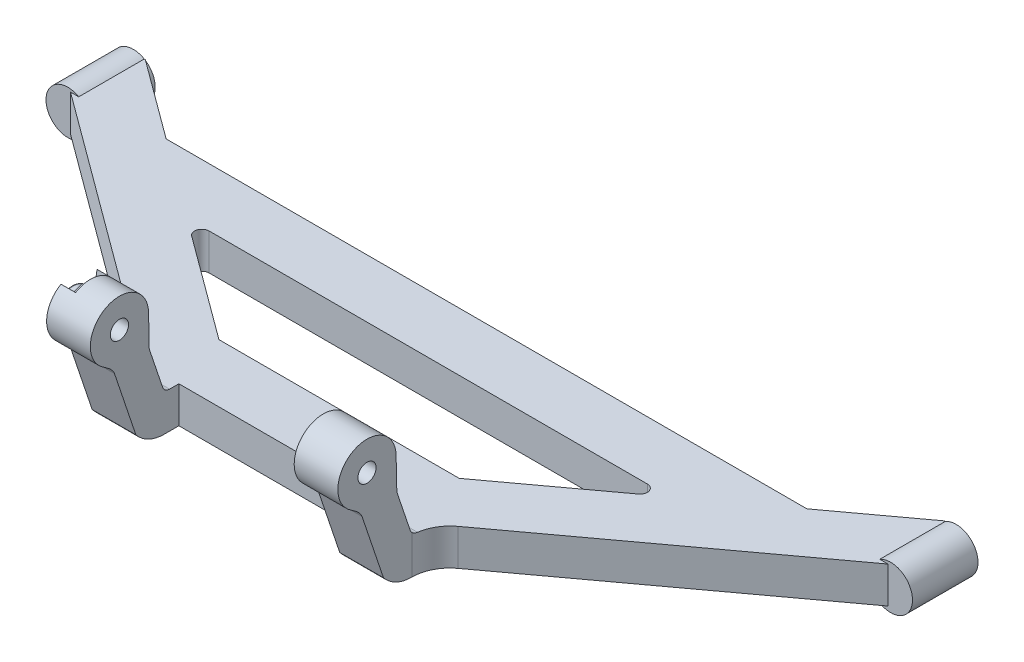
SolidWorks part; units mm, degrees
ref_plane "Front Plane" through (0, 0, 0) normal (0, 0, 1) x (1, 0, 0)
ref_plane "Top Plane" through (0, 0, 0) normal (0, 1, 0) x (1, 0, 0)
ref_plane "Right Plane" through (0, 0, 0) normal (1, 0, 0) x (0, 0, -1)
sketch "Sketch1" plane through (0, 0, 0) normal (0, 1, 0) x (1, 0, 0)
  line L0 (-16.5, 0) -> (16.5, 0)
  line L1 (16.5, 0) -> (30.6842, 10.4448)
  line L2 (30.0913, 12.25) -> (-30.0913, 12.25)
  line L3 (-30.6842, 10.4448) -> (-16.5, 0)
  line L4 (-44, 20.25) -> (44, 20.25)
  line L5 (44, 20.25) -> (54.8642, 28.25)
  line L6 (54.8642, 28.25) -> (59.5, 28.25)
  line L7 (59.5, 28.25) -> (59.5, 19.25)
  line L8 (59.5, 19.25) -> (56.1339, 19.25)
  line L9 (56.1339, 19.25) -> (19.1277, -8)
  line L10 (19.1277, -8) -> (-19.1277, -8)
  line L11 (-19.1277, -8) -> (-56.1339, 19.25)
  line L12 (-56.1339, 19.25) -> (-59.5, 19.25)
  line L13 (-59.5, 19.25) -> (-59.5, 28.25)
  line L14 (-59.5, 28.25) -> (-54.8642, 28.25)
  line L15 (-54.8642, 28.25) -> (-44, 20.25)
  line L16 (0, 12.25) -> (0, 7.6782) construction
  line L17 (-59.5, 23.75) -> (59.5, 23.75) construction
  line L18 (0, 23.75) -> (0, 31.9049) construction
  line L19 (-14, -10) -> (-20, -10)
  line L20 (-14, -10) -> (-14, -8)
  line L21 (-20, -10) -> (-20, -10.0217) construction
  line L22 (14, -10) -> (20, -10)
  line L23 (14, -10) -> (14, -8)
  arc A0 (-20, -10) -> (-22.1277, -5.7909) centre (-25.2272, -10) ccw
  arc A1 (20, -10) -> (22.1277, -5.7909) centre (25.2272, -10) cw
  arc A2 (30.0913, 12.25) -> (30.6842, 10.4448) centre (30.0913, 11.25) cw
  arc A3 (-30.6842, 10.4448) -> (-30.0913, 12.25) centre (-30.0913, 11.25) cw
  point P19 (0, -8)
  point P29 (-20, -10.0217)
  dimension "D15" = 1
  dimension "D1" = 12.25
  dimension "D2" = 88
  dimension "D3" = 8
  dimension "D4" = 8
  dimension "D5" = 119
  dimension "D6" = 8
  dimension "D7" = 8
  dimension "D8" = 8
  dimension "D9" = 9
  dimension "D10" = 9
  dimension "D11" = 33
  dimension "D12" = 2
  dimension "D13" = 14
  dimension "D14" = 6
extrude "Boss-Extrude1" add sketch "Sketch1" along normal blind 5 contours L15 L14 L13 L12 L11 L10 L9 L8 L7 L6 L5 L4 L3 L2 L1 L0 | A0 L19 L20 L10 L11 | L22 A1 L9 L10 L23
sketch "Sketch2" plane through (0, 0, -28.25) normal (0, 0, -1) x (-1, 0, 0)
  line L0 (59.5, 5) -> (59.5, 0) construction
  circle A0 centre (56.5, 2.3998) radius 3
  dimension "D1" = 6
extrude "Boss-Extrude2" add sketch "Sketch2" against normal up to surface (9 mm away) up to face at (-57.8169, 2.5, -19.25)
sketch "Sketch3" plane through (0, 0, -28.25) normal (0, 0, -1) x (-1, 0, 0)
  line L0 (56.5, 5.3998) -> (60.6115, 5.3998)
  line L1 (60.6115, 5.3998) -> (60.6115, -0.6002)
  line L2 (60.6115, -0.6002) -> (56.5, -0.6002)
  circle A0 centre (56.5, 2.3998) radius 3
  arc A1 (54.8642, 4.9146) -> (54.6997, 0) centre (56.5, 2.3998) ccw construction
  arc M2 (54.8642, 4.9146) -> (58.3003, 0) centre (56.5, 2.3998) ccw
  line M3 (58.3003, 0) -> (59.5, 0)
  line M4 (59.5, 0) -> (59.5, 5)
  line M5 (59.5, 5) -> (57.9963, 5)
  arc M6 (57.9963, 5) -> (55.0037, 5) centre (56.5, 2.3998) ccw
extrude "Cut-Extrude2" cut sketch "Sketch3" against normal up to surface (9 mm away) contours L2 L1 L0 M6 M5 M4 M3 M2 | A0 M4 M5 | A0 M3 M4 up to face at (-57.1585, 2.4749, -19.25)
sketch "Sketch5" plane through (0, 0, -28.25) normal (0, 0, -1) x (-1, 0, 0)
  circle A0 centre (56.5, 2.3998) radius 1
  dimension "D1" = 2
extrude "Cut-Extrude3" cut sketch "Sketch5" against normal blind 7
mirror "Mirror1" about plane through (0, 0, 0) normal (1, 0, 0) of "Cut-Extrude3", "Cut-Extrude2", "Boss-Extrude2"
sketch "Sketch6" plane through (-14, 0, 0) normal (1, 0, 0) x (0, 0, -1)
  line L0 (-10, 5) -> (-12.8011, 13.3364)
  line L1 (-10, 0) -> (-8, 0) construction
  line L2 (-13.9031, 1.875) -> (-17.1813, 11.6311)
  line L3 (-16.4251, 8.4237) -> (-11.6855, 10.0163) construction
  line L4 (-14.0553, 9.22) -> (-13.3549, 7.1355) construction
  line L5 (-16.9448, 19.4233) -> (-23.523, 18.1167) construction
  line L6 (-16.1655, 19.5) -> (-12.8249, 19.5) construction
  line L7 (-10, 5) -> (-10, 0)
  line L8 (19.25, 0) -> (-5.7909, 0) construction
  line L9 (-12.1665, 15.5888) -> (-12.068, 11.1544)
  arc A0 (-10, 0) -> (-13.9031, 1.875) centre (-10, 5) cw
  circle A1 centre (-16.1655, 15.5) radius 4
  circle A2 centre (-16.1655, 15.5) radius 1.25
  spline S0 degree 2 poles (-18.3402, 12.1428) (-17.0786, 11.3256) (-16.8507, 10.6473) knots 0 0 0 1 1 1
  line M9 (-10, 5) -> (-10, 0)
  dimension "D1" = 8
  dimension "D2" = 2.5
  dimension "D3" = 15.5
  dimension "D4" = 5
  dimension "D5" = 19.5
extrude "Boss-Extrude3" add sketch "Sketch6" against normal blind 6 contours A1 L2 A0 L0 M9 | A1 S0 L2 | A1 A2 | A1 L0 L9
fillet "Fillet1" radius 1 1 edges at (-17, 5, 10)
mirror "Mirror3" about plane through (0, 0, 0) normal (1, 0, 0) of "Fillet1", "Boss-Extrude3"
sketch "Sketch7" plane through (-20, 0, 0) normal (-1, 0, 0) x (0, 0, 1)
  line L0 (13.4858, 16.5736) -> (13.2472, 18.2356)
  line L1 (18.8452, 14.4264) -> (18.435, 17.2839)
  line L2 (18.435, 17.2839) -> (15.7553, 18.3575)
  line L3 (15.7553, 18.3575) -> (13.4858, 16.5736)
  line L4 (13.4858, 16.5736) -> (13.8959, 13.7161)
  line L5 (13.8959, 13.7161) -> (16.5756, 12.6425)
  line L6 (16.5756, 12.6425) -> (18.8452, 14.4264)
  line L7 (18.435, 17.2839) -> (18.1965, 18.946)
  circle A0 centre (16.1655, 15.5) radius 2.5 construction
  arc A1 (18.3402, 12.1428) -> (12.1665, 15.5888) centre (16.1655, 15.5) ccw construction
  arc A2 (13.2472, 18.2356) -> (18.1965, 18.946) centre (16.1655, 15.5) cw
  point P1 (13.6908, 15.1448)
  arc M12 (18.3402, 12.1428) -> (12.1665, 15.5888) centre (16.1655, 15.5) ccw
  circle M13 centre (16.1655, 15.5) radius 1.25
  dimension "D1" = 5
extrude "Cut-Extrude4" cut sketch "Sketch7" against normal blind 2 contours L2 L7 L0 L3 M12 | L5 L6 L1 L2 L3 L4 M13
sketch "Sketch8" plane through (-18, 0, 0) normal (-1, 0, 0) x (0, 0, 1)
  line L0 (13.8959, 13.7161) -> (13.2472, 18.2356) construction
  line L1 (15.7964, 18.0717) -> (13.7537, 16.4662)
  line L2 (13.7537, 16.4662) -> (14.1229, 13.8945)
  line L3 (14.1229, 13.8945) -> (16.5346, 12.9283)
  line L4 (16.5346, 12.9283) -> (18.5772, 14.5338)
  line L5 (18.5772, 14.5338) -> (18.2081, 17.1055)
  line L6 (18.2081, 17.1055) -> (15.7964, 18.0717)
  circle A0 centre (16.1655, 15.5) radius 2.25 construction
  circle A1 centre (16.1655, 15.5) radius 1.25
  circle A2 centre (16.1655, 15.5) radius 1.25 construction
  dimension "D1" = 4.5
extrude "Boss-Extrude4" add sketch "Sketch8" along normal blind 1.5
sketch "Sketch9" plane through (-19.5, 0, 0) normal (-1, 0, 0) x (0, 0, 1)
  circle A0 centre (16.1655, 15.5) radius 1.25
  circle A1 centre (16.1655, 15.5) radius 2.105
  circle A2 centre (16.1655, 15.5) radius 1.25 construction
extrude "Boss-Extrude5" add sketch "Sketch9" along normal blind 1
fillet "Fillet2" radius 0.25 1 edges at (-20.5, 15.5, 18.2704)
